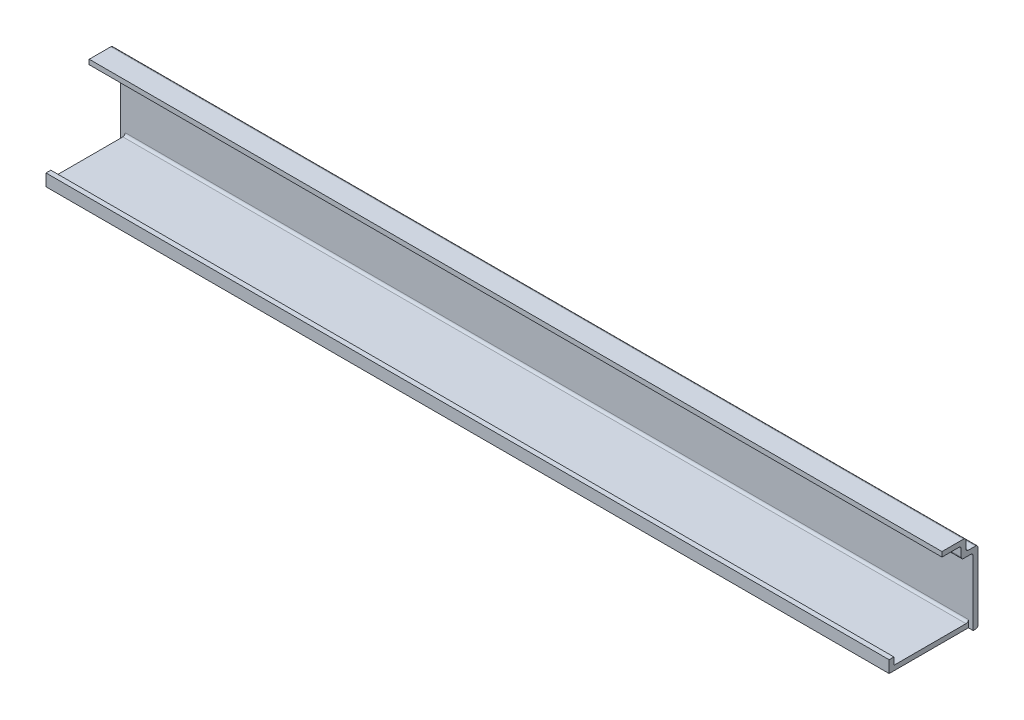
SolidWorks part; units mm, degrees
ref_plane "Front Plane" through (0, 0, 0) normal (0, 0, 1) x (1, 0, 0)
ref_plane "Top Plane" through (0, 0, 0) normal (0, 1, 0) x (1, 0, 0)
ref_plane "Right Plane" through (0, 0, 0) normal (1, 0, 0) x (0, 0, -1)
sketch "Sketch6" plane through (0, 0, 0) normal (1, 0, 0) x (0, 0, -1)
  line L0 (0, 3) -> (0, 0)
  line L1 (0, 0) -> (31, 0)
  line L2 (31, 0) -> (31, 26)
  line L3 (31, 26) -> (26, 26)
  line L4 (26, 26) -> (26, 31)
  line L5 (26, 31) -> (18, 31)
  line L6 (18, 31) -> (18, 33)
  line L7 (18, 33) -> (28, 33)
  line L8 (28, 33) -> (28, 28)
  line L9 (28, 28) -> (33, 28)
  line L10 (33, 28) -> (33, -2)
  line L11 (33, -2) -> (-2, -2)
  line L12 (-2, -2) -> (-2, 3)
  line L13 (-2, 3) -> (0, 3)
  dimension "D1" = 2
  dimension "D2" = 2
  dimension "D3" = 2
  dimension "D4" = 2
  dimension "D5" = 2
  dimension "D6" = 2
  dimension "D7" = 35
  dimension "D8" = 5
  dimension "D9" = 5
  dimension "D10" = 10
  dimension "D11" = 5
  dimension "D12" = 30
extrude "Boss-Extrude5" add sketch "Sketch6" against normal blind 355
sketch "Sketch7" plane through (0, 0, 2) normal (0, 0, 1) x (1, 0, 0)
  line L1 (0, -2) -> (-2, -2)
  line L2 (0, -2) -> (0, 25.9466)
  line L3 (0, 25.9466) -> (-2, 25.9466)
  line L4 (-2, -2) -> (-2, 25.9466)
  point P5 (0, 39.1328)
  point P6 (0, 25.9466)
  dimension "D1" = 2
extrude "Cut-Extrude1" cut sketch "Sketch7" against normal up to surface (33 mm away) up to face at (-177.5, 13, -31)
sketch "Sketch8" plane through (0, 0, 2) normal (0, 0, 1) x (1, 0, 0)
  line L0 (-178.5, -2) -> (-178.5, 68.8052) construction
  line L1 (-355, -2) -> (-2, -2) construction
sketch "Sketch9" plane through (0, 0, 2) normal (0, 0, 1) x (1, 0, 0)
  line L0 (-355, 26) -> (0, 26) construction
  line L1 (-355, -2) -> (-353, -2)
  line L2 (-355, -2) -> (-355, 26)
  line L3 (-355, 26) -> (-353, 26)
  line L4 (-353, -2) -> (-353, 26)
  point P5 (-348.4534, 26)
  dimension "D1" = 2
extrude "Cut-Extrude2" cut sketch "Sketch9" against normal up to surface (33 mm away) up to face at (-119, 8, -31)
fillet "Fillet4" radius 1 5 edges at (-177.5, 28, -28) (-177.5, 33, -28) (-177.5, 31, -26) (-177.5, 26, -31) (-177.5, 28, -33)
fillet "Fillet5" radius 1 1 edges at (-177.5, -2, -33)
fillet "Fillet6" radius 1 1 edges at (-177.5, 0, -31)
fillet "Fillet7" radius 1 1 edges at (-177.5, 26, -26)
